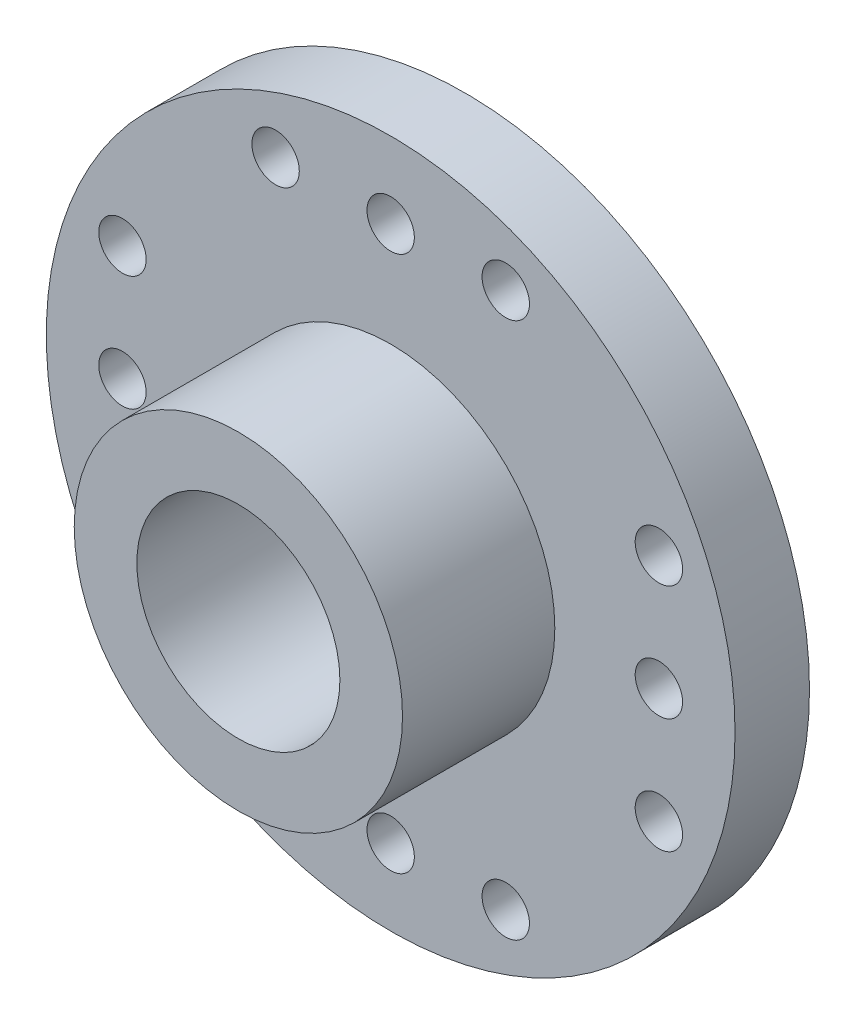
SolidWorks part; units mm, degrees
ref_plane "前基準面" through (0, 0, 0) normal (0, 0, 1) x (1, 0, 0)
ref_plane "上基準面" through (0, 0, 0) normal (0, 1, 0) x (1, 0, 0)
ref_plane "右基準面" through (0, 0, 0) normal (1, 0, 0) x (0, 0, -1)
sketch "草圖1" plane through (0, 0, 0) normal (0, 0, 1) x (1, 0, 0)
  circle A0 centre (0, 0) radius 10.175
  circle A1 centre (0, 0) radius 1.375
  circle A2 centre (7.925, 0) radius 0.7
  circle A3 centre (7.925, 3.4) radius 0.7
  circle A4 centre (7.925, -3.4) radius 0.7
  circle A5 centre (-7.925, 0) radius 0.7
  circle A8 centre (-7.925, 3.4) radius 0.7
  circle A9 centre (-7.925, -3.4) radius 0.7
  circle A10 centre (0, -7.925) radius 0.7
  circle A11 centre (-3.4, -7.925) radius 0.7
  circle A12 centre (3.4, -7.925) radius 0.7
  circle A13 centre (0, 7.925) radius 0.7
  circle A14 centre (3.4, 7.925) radius 0.7
  circle A15 centre (-3.4, 7.925) radius 0.7
  dimension "D1" = 2.75
  dimension "D2" = 20.35
  dimension "D3" = 1.4
  dimension "D5" = 1.4
  dimension "D6" = 1.4
  dimension "D10" = 1.4
  dimension "D11" = 1.4
  dimension "D13" = 1.4
  dimension "D14" = 1.4
  dimension "D15" = 1.4
  dimension "D18" = 1.4
  dimension "D20" = 1.4
  dimension "D21" = 1.4
  dimension "D4" = 7.925
  dimension "D7" = 3.4
  dimension "D8" = 3.4
  dimension "D9" = 7.925
  dimension "D12" = 7.925
  dimension "D16" = 3.4
  dimension "D17" = 3.4
  dimension "D19" = 7.925
extrude "填料-伸長1" add sketch "草圖1" along normal blind 2.2 contours A9 | A8 | A5 | A4 | A3 | A2 | A1 | A0 | A15 | A14 | A13 | A12 | A11 | A10
sketch "草圖2" plane through (0, 0, 2.2) normal (0, 0, 1) x (1, 0, 0)
  circle A0 centre (0, 0) radius 4.85
  circle A1 centre (0, 0) radius 3
  dimension "D1" = 9.7
  dimension "D2" = 6
extrude "填料-伸長2" add sketch "草圖2" along normal blind 4.5
